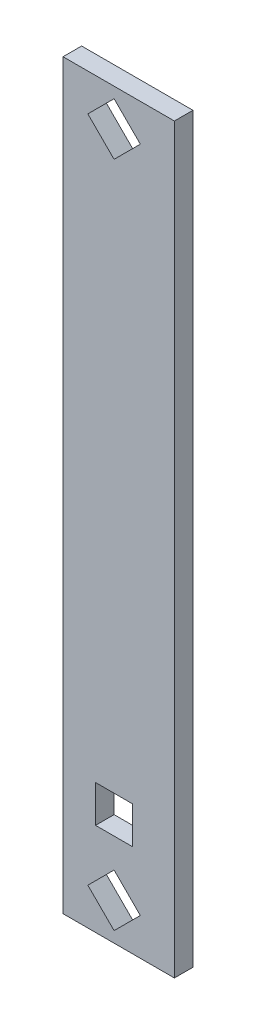
SolidWorks part; units mm, degrees
ref_plane "Top" through (0, 0, 0) normal (0, 0, 1) x (1, 0, 0)
ref_plane "Front" through (0, 0, 0) normal (0, 1, 0) x (1, 0, 0)
ref_plane "Right" through (0, 0, 0) normal (1, 0, 0) x (0, 0, -1)
sketch "Profile Sketch" plane through (-13.8341, 0, -105.7567) normal (0, 1, 0) x (-1, 0, 0)
  line L1 (-3, 0) -> (3, 0)
  line L2 (-3, 0) -> (-3, 1)
  line L3 (-3, 1) -> (3, 1)
  line L4 (3, 0) -> (3, 1)
  line L5 (0, 1) -> (0, 0) construction
  line L6 (-3, 0.5) -> (3, 0.5) construction
  point P128 (0, 0.5)
  dimension "Height" = 1
  dimension "Width" = 6
extrude "Profile Extrude" add sketch "Profile Sketch" along normal blind 40
sketch "Fiducial Sketch" plane through (0, 0, -104.7567) normal (0, 0, 1) x (1, 0, 0)
  line L0 (-14.0841, 2) -> (-12.6698, 2) construction
  line L1 (-12.6698, 2) -> (-14.0841, 3.4142)
  line L2 (-14.0841, 3.4142) -> (-15.4983, 2)
  line L3 (-15.4983, 2) -> (-14.0841, 0.5858)
  line L4 (-14.0841, 0.5858) -> (-12.6698, 2)
  line L9 (-14.0841, 2) -> (-14.0841, 0) construction
  line L10 (-16.8341, 0) -> (-10.8341, 0) construction
  line L17 (-16.8341, 40) -> (-16.8341, 0) construction
  circle A0 centre (-14.0841, 2) radius 1.4142 construction
  point P85 (-14.0841, 4)
  dimension "D1" = 2.8284
  dimension "Fiducial Y Spacing" = 2
  dimension "Fiducial X Position" = 2.75
extrude "Fiducial Cut" cut sketch "Fiducial Sketch" against normal through all
ref_plane "Mid Plane" through (0, 20, 0) normal (0, -1, 0) x (-1, 0, 0)
mirror "Fiducial Mirror" about plane through (0, 20, 0) normal (0, -1, 0) of "Fiducial Cut"
sketch "Fiducial 1 Indicator Sketch" plane through (0, 0, -104.7567) normal (0, 0, 1) x (1, 0, 0)
  line L9 (-14.0841, 2) -> (-14.0841, 0) construction
  line L11 (-15.0841, 4) -> (-13.0841, 4) construction
  line L12 (-15.0841, 7) -> (-13.0841, 7)
  line L13 (-15.0841, 7) -> (-15.0841, 5)
  line L14 (-15.0841, 5) -> (-13.0841, 5)
  line L15 (-13.0841, 7) -> (-13.0841, 5)
  line L16 (-14.0841, 5) -> (-14.0841, 7) construction
  line L17 (-15.0841, 6) -> (-13.0841, 6) construction
  line L18 (-16.8341, 0) -> (-10.8341, 0) construction
  line L19 (-16.8341, 40) -> (-16.8341, 0) construction
  point P85 (-14.0841, 6)
  dimension "Fiducial X Position" = 2.75
  dimension "D2" = 2.8284
extrude "Fiducial 1 Indicator Cut" cut sketch "Fiducial 1 Indicator Sketch" against normal through all
equation "\"D1@Fiducial Sketch\" = 2 * sqr ( 2 ) "
equation "\"D2@Fiducial 1 Indicator Sketch\" = 2 * sqr ( 2 ) "
